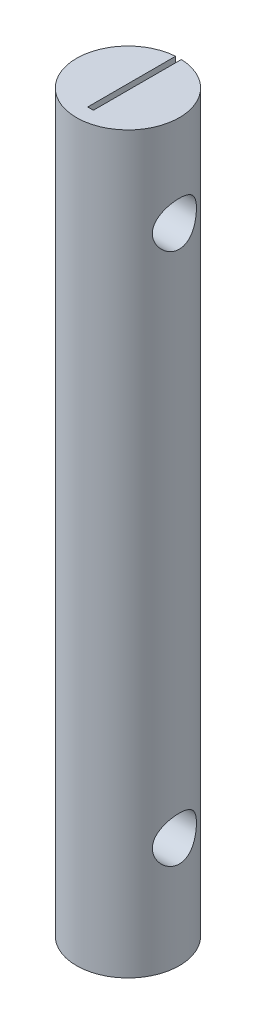
SolidWorks part; units mm, degrees
ref_plane "Front Plane" through (0, 0, 0) normal (0, 0, 1) x (1, 0, 0)
ref_plane "Top Plane" through (0, 0, 0) normal (0, 1, 0) x (1, 0, 0)
ref_plane "Right Plane" through (0, 0, 0) normal (1, 0, 0) x (0, 0, -1)
sketch "Sketch1" plane through (0, 0, 0) normal (0, 1, 0) x (1, 0, 0)
  circle A0 centre (0, 0) radius 7
  dimension "D1" = 14
extrude "Boss-Extrude1" add sketch "Sketch1" along normal blind 100
sketch "Sketch2" plane through (0, 100, 0) normal (0, 1, 0) x (1, 0, 0)
  line L0 (0, 0) -> (7.1226, 0) construction
  line L1 (7.1226, 0) -> (-7.4051, 0) construction
  line L2 (-7.4051, 0) -> (-0.1412, 0) construction
  line L3 (-0.1412, 0) -> (-0.1412, 6.9986) construction
  line L4 (-0.1412, 6.9986) -> (-0.1412, -7.617) construction
  line L5 (6.7761, 0) -> (6.7761, 6.2955) construction
  line L6 (-0.5, 7.4036) -> (0.2761, 7.4036)
  line L7 (-0.5, 7.4036) -> (-0.5, -4.9799)
  line L8 (-0.5, -4.9799) -> (0.2761, -4.9799)
  line L9 (0.2761, 7.4036) -> (0.2761, -4.9799)
  line L10 (6.7761, 6.2955) -> (6.7761, -3.4144) construction
  line L11 (-7, 0) -> (-7, 6.2955) construction
  line L12 (-7, 6.2955) -> (-7, -7.617) construction
  line L13 (-0.1412, -6.9799) -> (-7.2013, -6.9799) construction
  line L14 (-7.2013, -6.9799) -> (8.3265, -6.9799) construction
  circle A0 centre (0, 0) radius 7 construction
  point P19 (-0.112, -4.9799)
  dimension "D1" = 6.5
  dimension "D2" = 6.5
  dimension "D3" = 2
extrude "Cut-Extrude1" cut sketch "Sketch2" against normal blind 40
sketch "Sketch3" plane through (0, 0, 0) normal (1, 0, 0) x (0, 0, -1)
  line L0 (-0.0027, 15) -> (-0.0027, -18.7828) construction
  line L1 (-0.0027, -18.7828) -> (-0.0027, 23.7628) construction
  line L2 (11.2967, 15) -> (-12.0516, 15) construction
  line L3 (-7, 0) -> (7, 0) construction
  line L4 (0, 0) -> (0, 102.4957) construction
  line L5 (0, 102.4957) -> (0, 51.2479) construction
  line L6 (0, 51.2479) -> (-10.7758, 51.2479) construction
  line L7 (-10.7758, 51.2479) -> (28.9416, 51.2479) construction
  circle A0 centre (-0.0027, 15) radius 3
  circle A1 centre (-0.0027, 87.4957) radius 3
  dimension "D1" = 6
  dimension "D2" = 15
extrude "Cut-Extrude2" cut sketch "Sketch3" against normal blind 40 and the other way blind 40
